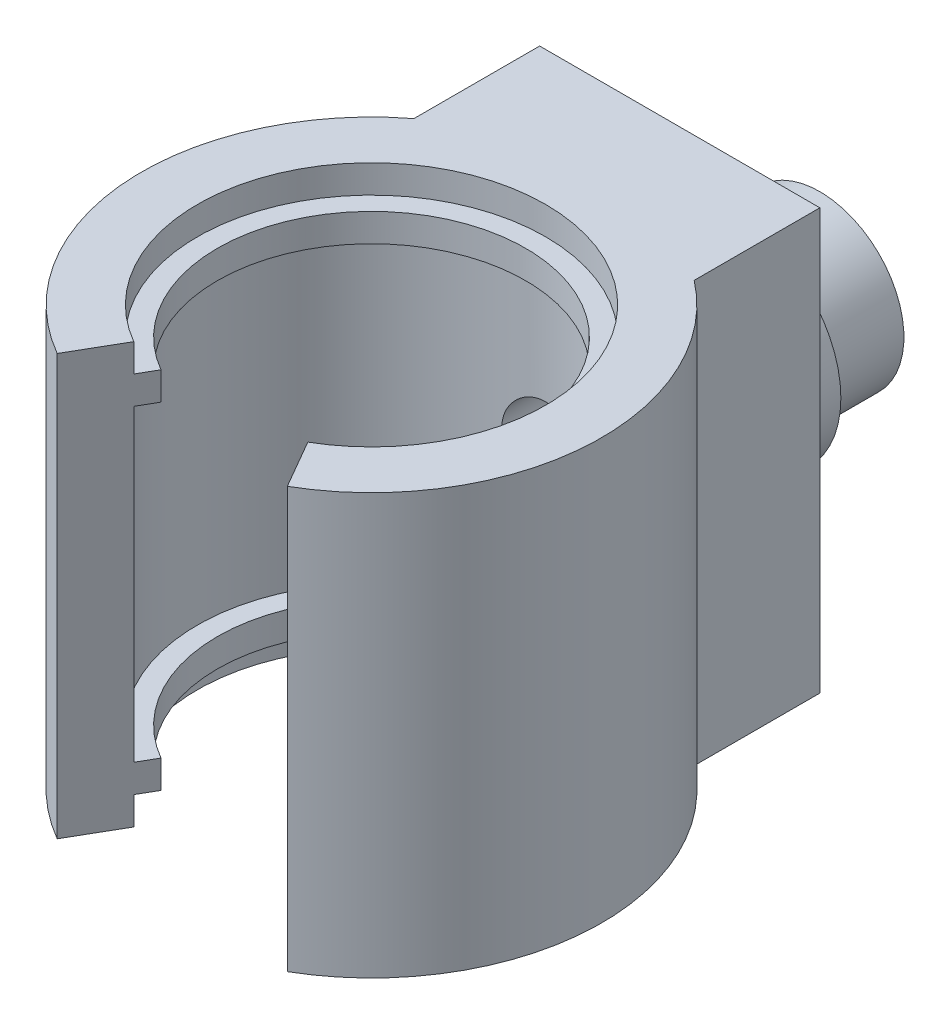
SolidWorks part; units mm, degrees
ref_plane "Front Plane" through (0, 0, 0) normal (0, 0, 1) x (1, 0, 0)
ref_plane "Top Plane" through (0, 0, 0) normal (0, 1, 0) x (1, 0, 0)
ref_plane "Right Plane" through (0, 0, 0) normal (1, 0, 0) x (0, 0, -1)
sketch "Sketch1" plane through (0, 0, 0) normal (0, 1, 0) x (1, 0, 0)
  line L0 (-5, 6.5135) -> (5, 6.5135) construction
  line L1 (-5, 6.5135) -> (0, 0) construction
  line L2 (0, 0) -> (5, 6.5135) construction
  line L3 (-5, 6.5135) -> (-5, 11)
  line L4 (5, 6.5135) -> (5, 11)
  line L5 (-5, 11) -> (5, 11)
  line L6 (0, 0) -> (0, 11) construction
  circle A0 centre (0, 0) radius 6.2113
  arc A1 (-5, 6.5135) -> (5, 6.5135) centre (0, 0) ccw
  dimension "D1" = 10
  dimension "D3" = 11
  dimension "D2" = 2
extrude "Boss-Extrude1" add sketch "Sketch1" along normal blind 15
sketch "Sketch2" plane through (0, 0, -11) normal (0, 0, -1) x (-1, 0, 0)
sketch "Sketch4" plane through (0, 15, 0) normal (0, 1, 0) x (1, 0, 0)
  line L0 (-3.1056, -5.3791) -> (-4.1056, -7.1112)
  line L1 (3.1056, -5.3791) -> (4.1056, -7.1112)
  line L2 (0, 0) -> (-4.1056, -7.1112) construction
  line L3 (0, 0) -> (4.1056, -7.1112) construction
  line L5 (-4.1056, -7.1112) -> (4.1056, -7.1112) construction
  circle A0 centre (0, 0) radius 6.2113 construction
  arc A1 (-5, 6.5135) -> (5, 6.5135) centre (0, 0) ccw construction
  arc A2 (-3.1056, -5.3791) -> (3.1056, -5.3791) centre (0, 0) ccw
  arc A3 (-4.1056, -7.1112) -> (4.1056, -7.1112) centre (0, 0) ccw
  dimension "D1" = 60
extrude "Cut-Extrude1" cut sketch "Sketch4" against normal through all both and the other way through all
ref_plane "Plane2" through (0, 1, 0) normal (0, -1, 0) x (-1, 0, 0)
sketch "Sketch5" plane through (0, 1, 0) normal (0, -1, 0) x (-1, 0, 0)
  line L0 (3.1056, -5.3791) -> (2.75, -4.7631)
  line L1 (-2.75, -4.7631) -> (-3.1056, -5.3791)
  line L2 (-4.1056, -7.1112) -> (-3.1056, -5.3791) construction
  arc A0 (2.75, -4.7631) -> (-2.75, -4.7631) centre (0, 0) ccw
  arc A1 (-3.1056, -5.3791) -> (3.1056, -5.3791) centre (0, 0) cw
extrude "Boss-Extrude3" add sketch "Sketch5" against normal blind 1
ref_plane "Plane3" through (0, 7.5, 0) normal (0, 1, 0) x (1, 0, 0)
mirror "Mirror1" about plane through (0, 7.5, 0) normal (0, 1, 0) of "Boss-Extrude3"
sketch "Sketch6" plane through (0, 0, -11) normal (0, 0, -1) x (-1, 0, 0)
  line L0 (8.8, 7.5) -> (-8.8, 7.5) construction
  line L1 (0, 15) -> (0, 0) construction
  line L2 (-5, 15) -> (5, 15) construction
  circle A0 centre (0, 7.5) radius 1.4
  dimension "D1" = 2.8
extrude "Cut-Extrude2" cut sketch "Sketch6" against normal blind 10 contours A0
sketch "Sketch7" plane through (0, 0, -11) normal (0, 0, -1) x (-1, 0, 0)
  circle A0 centre (0, 7.5) radius 3.75
  dimension "D1" = 7.5
extrude "Boss-Extrude4" add sketch "Sketch7" along normal blind 2
sketch "Sketch8" plane through (0, 0, -13) normal (0, 0, -1) x (-1, 0, 0)
  circle A0 centre (0, 7.5) radius 3
  circle A1 centre (0, 7.5) radius 3.75 construction
  dimension "D1" = 6
extrude "Boss-Extrude5" add sketch "Sketch8" along normal blind 3
sketch "Sketch9" plane through (0, 0, -16) normal (0, 0, -1) x (-1, 0, 0)
  circle A0 centre (0, 7.5) radius 1.4
  dimension "D1" = 2.8
extrude "Cut-Extrude3" cut sketch "Sketch9" against normal through all both and the other way through all
